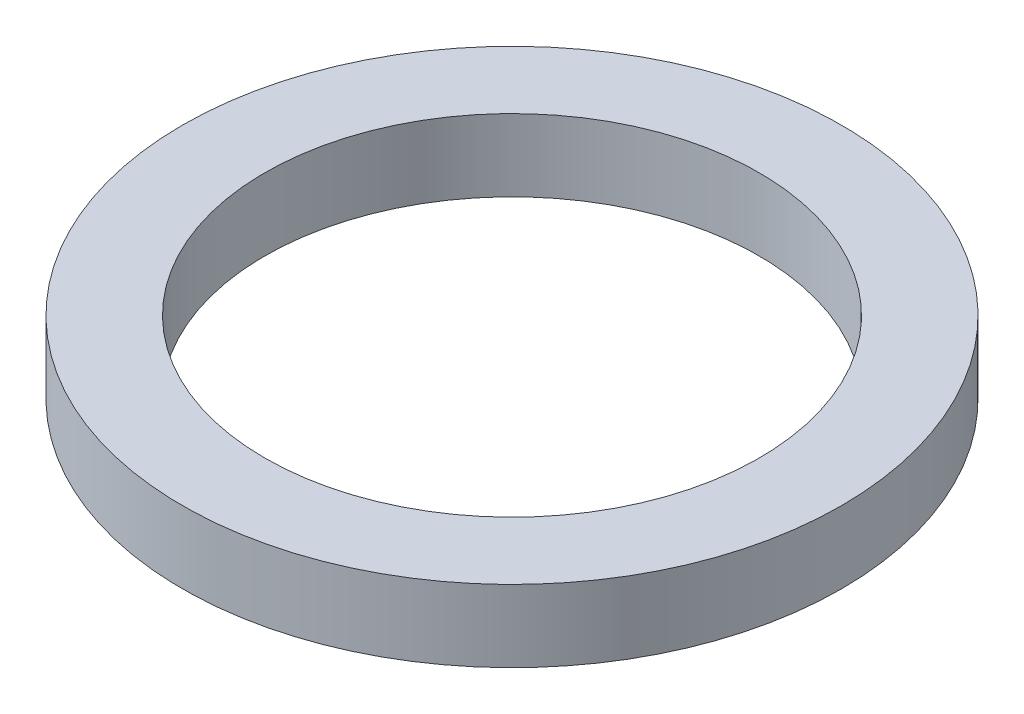
SolidWorks part; units mm, degrees
ref_plane "Front Plane" through (0, 0, 0) normal (0, 0, 1) x (1, 0, 0)
ref_plane "Top Plane" through (0, 0, 0) normal (0, 1, 0) x (1, 0, 0)
ref_plane "Right Plane" through (0, 0, 0) normal (1, 0, 0) x (0, 0, -1)
sketch "Sketch1" plane through (0, 0, 0) normal (0, 1, 0) x (1, 0, 0)
  circle A0 centre (0, 0) radius 6
  dimension "D1" = 12
extrude "Extrude-Thin1" add sketch "Sketch1" along normal blind 1.75 thin
